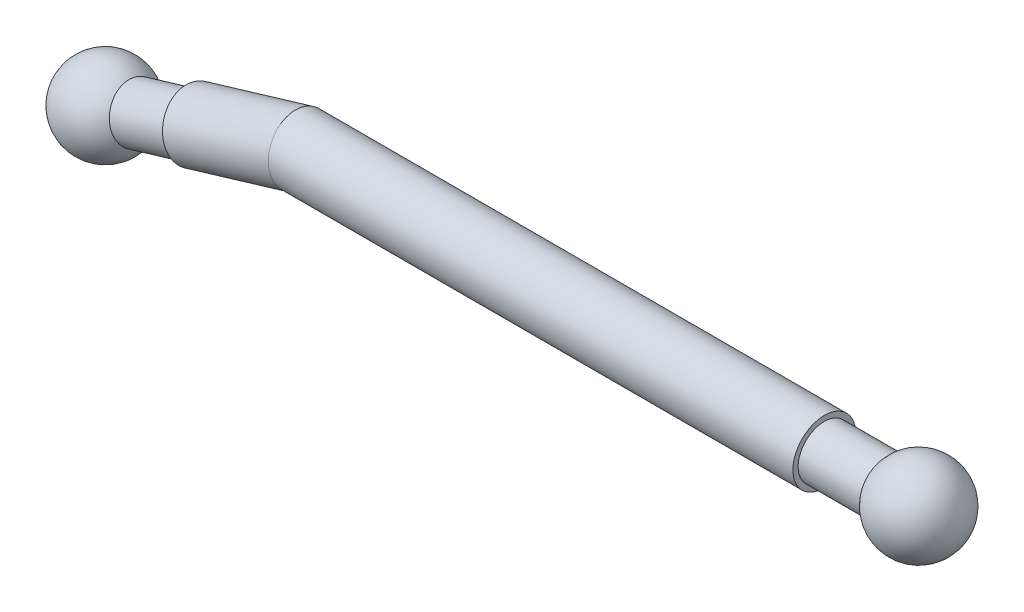
SolidWorks part; units mm, degrees
ref_plane "Front Plane" through (0, 0, 0) normal (0, 0, 1) x (1, 0, 0)
ref_plane "Top Plane" through (0, 0, 0) normal (0, 1, 0) x (1, 0, 0)
ref_plane "Right Plane" through (0, 0, 0) normal (1, 0, 0) x (0, 0, -1)
sketch "Sketch1" plane through (0, 0, 0) normal (1, 0, 0) x (0, 0, -1)
  circle A0 centre (0, 0) radius 3
  dimension "D1" = 6
sketch "Sketch2" plane through (0, 0, 0) normal (0, 0, 1) x (1, 0, 0)
  line L0 (0, 0) -> (-50, 0)
  line L1 (-50, 0) -> (-60, 0) construction
  line L2 (-60, 0) -> (-60, -3) construction
  line L3 (-50, 0) -> (-60, -3)
  dimension "D1" = 50
  dimension "D2" = 10
  dimension "D3" = 3
sweep "Sweep2" add profiles "Sketch1" path "Sketch2"
sketch "Sketch3" plane through (-55.8716, -16.7615, 0) normal (-0.9578, -0.2873, 0) x (0, 0, 1)
  circle A0 centre (0, 14.2332) radius 2.5
  point P2 (0, 0)
  point P3 (0, 11.5296)
  point P4 (0, 14.2332)
  dimension "D1" = 5
extrude "Boss-Extrude1" add sketch "Sketch3" along normal blind 6
ref_plane "Plane1" through (-64.492, -19.3476, 0) normal (-0.9578, -0.2873, 0) x (0, 0, 1)
sketch "Sketch4" plane through (-64.492, -19.3476, 0) normal (-0.9578, -0.2873, 0) x (0, 0, 1)
  line L0 (0, 18.2332) -> (0, 10.2332) construction
  line L1 (0, 18.2332) -> (0, 10.2332)
  arc A0 (0, 18.2332) -> (0, 10.2332) centre (0, 14.2332) cw
  point P3 (-0.4698, 11.9272)
  point P4 (0, 0)
  point P5 (0, 14.2332)
  point P6 (0.1181, 10.6218)
  point P7 (0, 0)
  point P8 (0, 11.5296)
  dimension "D2" = 8
revolve "Revolve1" add sketch "Sketch4" angle 360 about L0
sketch "Sketch5" plane through (0, 0, 0) normal (1, 0, 0) x (0, 0, -1)
  circle A0 centre (0, 0) radius 2.5
  dimension "D1" = 5
extrude "Boss-Extrude2" add sketch "Sketch5" along normal blind 6
ref_plane "Plane2" through (9, 0, 0) normal (1, 0, 0) x (0, 0, -1)
sketch "Sketch6" plane through (9, 0, 0) normal (1, 0, 0) x (0, 0, -1)
  line L0 (0, 4) -> (0, -4)
  arc A0 (0, 4) -> (0, -4) centre (0, 0) cw
  point P5 (0, 0)
  dimension "D2" = 8
revolve "Revolve2" add sketch "Sketch6" angle 360 about L0
